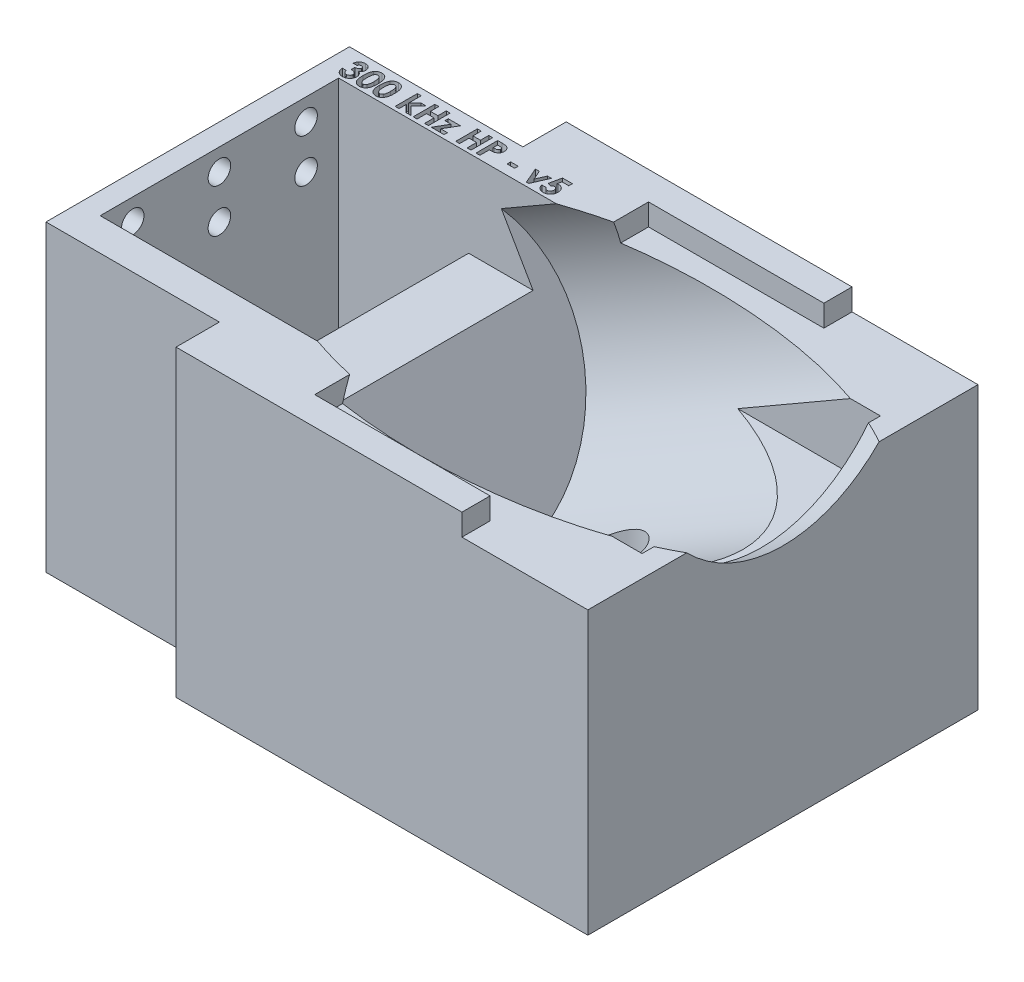
SolidWorks part; units mm, degrees
ref_plane "Front Plane" through (0, 0, 0) normal (0, 0, 1) x (1, 0, 0)
ref_plane "Top Plane" through (0, 0, 0) normal (0, 1, 0) x (1, 0, 0)
ref_plane "Right Plane" through (0, 0, 0) normal (1, 0, 0) x (0, 0, -1)
sketch "Sketch1" plane through (0, 0, 0) normal (0, 0, 1) x (1, 0, 0)
  line L1 (-139.7, -127) -> (88.9, -127)
  line L2 (-139.7, -127) -> (-139.7, 0)
  line L3 (-139.7, 0) -> (88.9, 0)
  line L4 (88.9, -127) -> (88.9, 0)
  line L5 (-139.7, -127) -> (88.9, 0) construction
  line L6 (-139.7, 0) -> (88.9, -127) construction
  point P0 (0, 0)
  dimension "D1" = 228.6
  dimension "D2" = 127
  dimension "D3" = 88.9
extrude "Boss-Extrude1" add sketch "Sketch1" along normal mid plane 101.6
sketch "Sketch10" plane through (0, -127, 0) normal (0, -1, 0) x (1, 0, 0)
  circle A0 centre (0, 0) radius 12.7
  dimension "D1" = 25.4
extrude "Cut-Extrude6" cut sketch "Sketch10" against normal through all
sketch "Sketch2" plane through (0, 0, 0) normal (0, 0, 1) x (1, 0, 0)
  line L0 (-48.125, -30.325) -> (0, -2.54) construction
  line L1 (0, 46.5867) -> (-47.9201, 18.9201)
  line L2 (-50.1425, -26.8306) -> (-69.3975, 6.5201)
  line L3 (-69.3975, 6.5201) -> (-47.9201, 18.9201)
  line L4 (-50.1425, -26.8306) -> (-48.125, -30.325)
  line L5 (-26.6476, -17.925) -> (-47.9201, 18.9201) construction
  line L7 (0, -2.54) -> (87.9882, 48.26)
  line L8 (-83.8, -2.54) -> (0, -2.54) construction
  line L10 (0, -2.54) -> (-48.125, -30.325)
  line L11 (88.9, 0) -> (-139.7, 0) construction
  line L12 (87.9882, 48.26) -> (66.7157, 85.1051)
  line L13 (0, 46.5867) -> (0, -2.54) construction
  line L17 (66.7157, 85.1051) -> (0, 46.5867)
  point P23 (-26.6476, -17.925)
  dimension "D1" = 30
  dimension "D2" = 24.8
  dimension "D3" = 2.54
  dimension "D4" = 30.77
  dimension "D5" = 42.545
  dimension "D6" = 101.6
revolve "Cut-Revolve1" cut sketch "Sketch2" angle 360 about L0
sketch "Sketch11" plane through (0, -127, 0) normal (0, -1, 0) x (1, 0, 0)
  line L1 (13, 13) -> (-13, 13)
  line L2 (13, 13) -> (13, -13)
  line L3 (13, -13) -> (-13, -13)
  line L4 (-13, 13) -> (-13, -13)
  line L5 (13, 13) -> (-13, -13) construction
  line L6 (13, -13) -> (-13, 13) construction
  point P0 (0, 0)
  dimension "D1" = 26
sketch "Sketch22" plane through (0, 0, 0) normal (0, 1, 0) x (1, 0, 0)
  line L0 (-41.275, -50.8) -> (-139.7, -50.8) construction
  line L1 (-139.7, 50.8) -> (-114.3, 50.8)
  line L2 (-139.7, 50.8) -> (-139.7, -50.8)
  line L3 (-139.7, -50.8) -> (-114.3, -50.8)
  line L4 (-114.3, 50.8) -> (-114.3, -50.8)
  dimension "D1" = 25.4
extrude "Cut-Extrude17" cut sketch "Sketch22" against normal through all
sketch "Sketch23" plane through (0, -127, 0) normal (0, -1, 0) x (1, 0, 0)
  line L0 (-127, 127) -> (127, -127) construction
  line L1 (-127, 127) -> (127, 127)
  line L2 (-127, 127) -> (-127, -127)
  line L3 (-127, -127) -> (127, -127)
  line L4 (127, 127) -> (127, -127)
  dimension "D1" = 254
  dimension "D2" = 254
extrude "Cut-Extrude18" cut sketch "Sketch23" against normal blind 38.1
sketch "Sketch21" plane through (0, 0, 0) normal (0, 1, 0) x (1, 0, 0)
  line L1 (88.9, -50.8) -> (57.15, -50.8)
  line L2 (88.9, -50.8) -> (88.9, 50.8)
  line L3 (88.9, 50.8) -> (57.15, 50.8)
  line L4 (57.15, -50.8) -> (57.15, 50.8)
  line L5 (88.9, -50.8) -> (-114.3, -50.8) construction
  line L6 (88.9, 50.8) -> (-114.3, 50.8) construction
  line L7 (-114.3, -50.8) -> (-114.3, 50.8) construction
  dimension "D1" = 171.45
extrude "Cut-Extrude16" cut sketch "Sketch21" against normal through all
sketch "Sketch26" plane through (0, 0, 0) normal (0, 1, 0) x (1, 0, 0)
  line L0 (57.15, 50.8) -> (57.15, 33.3829) construction
  line L1 (-107.95, -34.925) -> (50.8, -34.925)
  line L2 (-107.95, -34.925) -> (-107.95, 34.925)
  line L3 (-107.95, 34.925) -> (50.8, 34.925)
  line L4 (50.8, -34.925) -> (50.8, 34.925)
  line L5 (-114.3, -50.8) -> (-114.3, 50.8) construction
  point P4 (-107.95, 0)
  dimension "D1" = 6.35
  dimension "D2" = 6.35
  dimension "D3" = 69.85
extrude "Cut-Extrude21" cut sketch "Sketch26" against normal blind 25.4
sketch "Sketch27" plane through (-114.3, 0, 0) normal (-1, 0, 0) x (0, 0, 1)
  line L0 (50.8, 0) -> (-50.8, 0) construction
  line L1 (-25.4, -6.35) -> (25.4, -6.35) construction
  line L2 (-25.4, -6.35) -> (-25.4, -19.05) construction
  line L3 (-25.4, -19.05) -> (25.4, -19.05) construction
  line L4 (25.4, -6.35) -> (25.4, -19.05) construction
  line L7 (-25.4, -19.05) -> (-25.4, -31.75) construction
  line L8 (-25.4, -31.75) -> (25.4, -31.75) construction
  line L9 (25.4, -19.05) -> (25.4, -31.75) construction
  circle A0 centre (-25.4, -6.35) radius 3.302
  circle A1 centre (0, -6.35) radius 3.302
  circle A2 centre (0, -19.05) radius 3.302
  circle A3 centre (25.4, -6.35) radius 3.302
  circle A4 centre (25.4, -19.05) radius 3.302
  circle A5 centre (-25.4, -19.05) radius 3.302
  circle A7 centre (-25.4, -31.75) radius 3.302 [skipped]
  circle A8 centre (0, -31.75) radius 3.302 [skipped]
  circle A9 centre (25.4, -31.75) radius 3.302 [skipped]
  point P4 (0, -6.35)
  dimension "D5" = 6.604
  dimension "D8" = 25.4
  dimension "D1" = 50.8
  dimension "D2" = 12.7
  dimension "D3" = 6.35
  dimension "D4" = 12.7
  dimension "D6" = 3
  dimension "D7" = 3
extrude "Cut-Extrude22" cut sketch "Sketch27" against normal up to next and the other way through all
sketch "Sketch28" plane through (0, 0, 0) normal (0, 1, 0) x (1, 0, 0)
  line L0 (-114.3, 36.0198) -> (-43.5568, 36.0198) construction
  line L3 (-114.3, -50.8) -> (-114.3, 50.8) construction
  text T0 "<b>300 kHz HP - v5</b>" font "Century Gothic" height 6.35
extrude "Cut-Extrude23" cut sketch "Sketch28" against normal blind 3.175
sketch "Sketch30" plane through (0, -25.4, 0) normal (0, 1, 0) x (1, 0, 0)
  circle A0 centre (-95.25, 25.4) radius 3.429
  circle A2 centre (-82.55, 25.4) radius 3.429
  circle A3 centre (-82.55, 12.7) radius 3.429
  circle A4 centre (-82.55, 0) radius 3.429
  circle A5 centre (-82.55, -12.7) radius 3.429
  circle A6 centre (-82.55, -25.4) radius 3.429
  circle A7 centre (-95.25, 12.7) radius 3.429
  circle A8 centre (-95.25, 0) radius 3.429
  circle A9 centre (-95.25, -12.7) radius 3.429
  circle A10 centre (-95.25, -25.4) radius 3.429
  dimension "D1" = 6.858
  dimension "D2" = 25.4
  dimension "D3" = 95.25
  dimension "D4" = 2
  dimension "D5" = 5
extrude "Cut-Extrude24" cut sketch "Sketch30" against normal through all
sketch "Sketch31" plane through (0, -25.4, 0) normal (0, 1, 0) x (1, 0, 0)
  line L0 (-107.95, -34.925) -> (-44.1937, -34.925) construction
  line L1 (-107.95, 34.925) -> (-69.85, 34.925)
  line L2 (-107.95, 34.925) -> (-107.95, -34.925)
  line L3 (-107.95, -34.925) -> (-69.85, -34.925)
  line L4 (-69.85, 34.925) -> (-69.85, -34.925)
  dimension "D1" = 38.1
extrude "Cut-Extrude25" cut sketch "Sketch31" against normal offset from surface (60.325 mm away) 3.175 up to face at (-82.55, -88.9, 28.829)
sketch "Sketch32" plane through (0, 0, 0) normal (0, 1, 0) x (1, 0, 0)
  line L0 (57.15, 50.8) -> (57.15, 33.3829) construction
  line L1 (-31.1262, 48.895) -> (57.15, 48.895)
  line L2 (-31.1262, 48.895) -> (-31.1262, -48.895)
  line L3 (-31.1262, -48.895) -> (57.15, -48.895)
  line L4 (57.15, 48.895) -> (57.15, -48.895)
  point P4 (57.15, 0)
  dimension "D1" = 97.79
extrude "Cut-Extrude26" cut sketch "Sketch32" against normal blind 6.35
sketch "Sketch33" plane through (0, 0, 0) normal (0, 1, 0) x (1, 0, 0)
  line L1 (57.15, 50.8) -> (20.2503, 50.8)
  line L2 (57.15, 50.8) -> (57.15, -50.8)
  line L3 (57.15, -50.8) -> (20.2503, -50.8)
  line L4 (20.2503, 50.8) -> (20.2503, -50.8)
  line L5 (57.15, -50.8) -> (-114.3, -50.8) construction
extrude "Cut-Extrude27" cut sketch "Sketch33" against normal blind 6.35
sketch "Sketch34" plane through (0, 0, 50.8) normal (0, 0, 1) x (1, 0, 0)
  line L6 (57.15, -6.35) -> (20.2503, -6.35)
  line L7 (20.2503, -6.35) -> (20.2503, 0)
  line L8 (20.2503, 0) -> (-114.3, 0)
  line L9 (-114.3, 0) -> (-114.3, -88.9)
  line L10 (-114.3, -88.9) -> (57.15, -88.9)
  line L11 (57.15, -88.9) -> (57.15, -6.35)
  line L12 (57.15, -6.35) -> (20.2503, -6.35)
  line L13 (20.2503, -6.35) -> (20.2503, 0)
  line L14 (20.2503, 0) -> (-114.3, 0)
  line L15 (-114.3, 0) -> (-114.3, -88.9)
  line L16 (-114.3, -88.9) -> (57.15, -88.9)
  line L17 (57.15, -88.9) -> (57.15, -6.35)
  dimension "D1" = 0
extrude "Boss-Extrude2" add sketch "Sketch34" along normal blind 6.35
sketch "Sketch35" plane through (0, 0, -50.8) normal (0, 0, -1) x (-1, 0, 0)
  line L6 (-20.2503, 0) -> (-20.2503, -6.35)
  line L7 (-20.2503, -6.35) -> (-57.15, -6.35)
  line L8 (-57.15, -6.35) -> (-57.15, -88.9)
  line L9 (-57.15, -88.9) -> (114.3, -88.9)
  line L10 (114.3, -88.9) -> (114.3, 0)
  line L11 (114.3, 0) -> (-20.2503, 0)
  line L12 (-20.2503, 0) -> (-20.2503, -6.35)
  line L13 (-20.2503, -6.35) -> (-57.15, -6.35)
  line L14 (-57.15, -6.35) -> (-57.15, -88.9)
  line L15 (-57.15, -88.9) -> (114.3, -88.9)
  line L16 (114.3, -88.9) -> (114.3, 0)
  line L17 (114.3, 0) -> (-20.2503, 0)
  dimension "D1" = 0
extrude "Boss-Extrude3" add sketch "Sketch35" along normal blind 6.35
sketch "Sketch36" plane through (0, 0, 0) normal (0, 1, 0) x (1, 0, 0)
  line L0 (-114.3, -57.15) -> (-114.3, 57.15) construction
  line L1 (-114.3, 57.15) -> (-63.5, 57.15)
  line L2 (-114.3, 57.15) -> (-114.3, 44.45)
  line L3 (-114.3, 44.45) -> (-63.5, 44.45)
  line L4 (-63.5, 57.15) -> (-63.5, 44.45)
  line L5 (-114.3, -57.15) -> (-63.5, -57.15)
  line L6 (-114.3, -57.15) -> (-114.3, -44.45)
  line L7 (-114.3, -44.45) -> (-63.5, -44.45)
  line L8 (-63.5, -57.15) -> (-63.5, -44.45)
  dimension "D1" = 50.8
  dimension "D2" = 12.7
extrude "Cut-Extrude28" cut sketch "Sketch36" against normal through all
